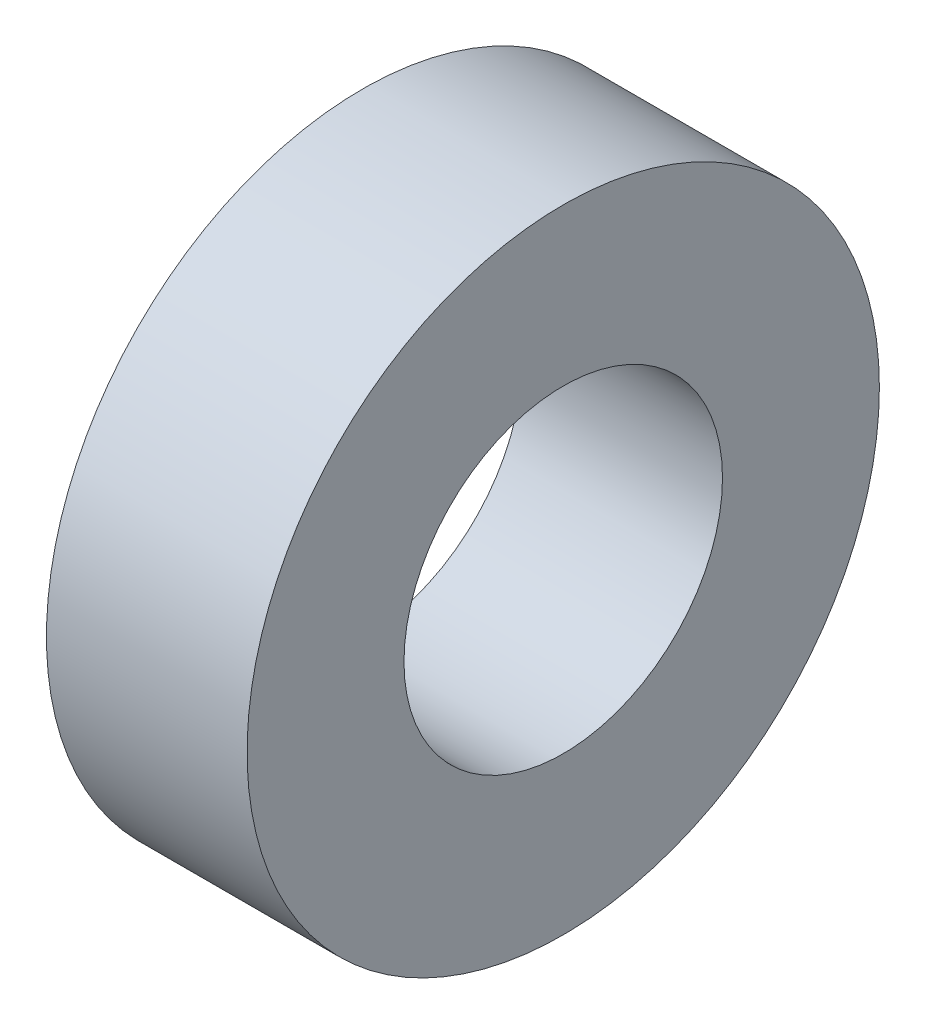
SolidWorks part; units mm, degrees
material "Hardboard"
ref_plane "Front Plane" through (0, 0, 0) normal (0, 0, 1) x (1, 0, 0)
ref_plane "Top Plane" through (0, 0, 0) normal (0, 1, 0) x (1, 0, 0)
ref_plane "Right Plane" through (0, 0, 0) normal (1, 0, 0) x (0, 0, -1)
sketch "Sketch2" plane through (0, 0, 0) normal (1, 0, 0) x (0, 0, -1)
  circle A0 centre (0, 0) radius 2.3813
  circle A1 centre (0, 0) radius 4.7272
  dimension "D1" = 4.7625
extrude "Boss-Extrude1" add sketch "Sketch2" along normal mid plane 3
